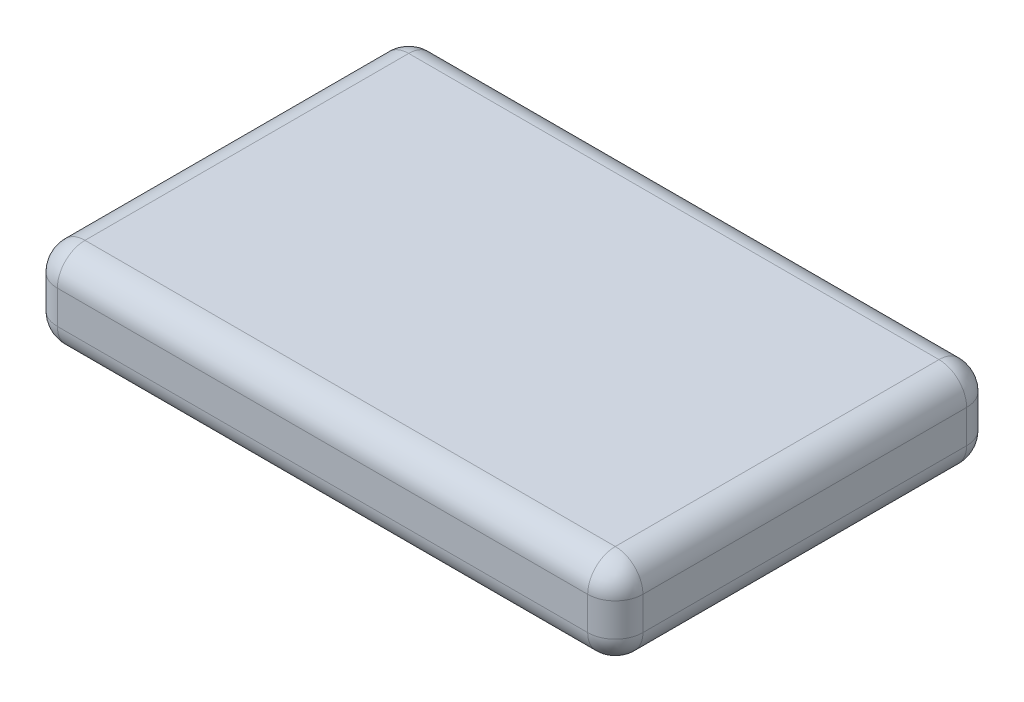
SolidWorks part; units mm, degrees
ref_plane "Front Plane" through (0, 0, 0) normal (0, 0, 1) x (1, 0, 0)
ref_plane "Top Plane" through (0, 0, 0) normal (0, 1, 0) x (1, 0, 0)
ref_plane "Right Plane" through (0, 0, 0) normal (1, 0, 0) x (0, 0, -1)
sketch "Sketch1" plane through (0, 0, 0) normal (0, 1, 0) x (1, 0, 0)
  line L1 (-53, -34.3) -> (53, -34.3)
  line L2 (-53, -34.3) -> (-53, 34.3)
  line L3 (-53, 34.3) -> (53, 34.3)
  line L4 (53, -34.3) -> (53, 34.3)
  line L5 (-53, -34.3) -> (53, 34.3) construction
  line L6 (-53, 34.3) -> (53, -34.3) construction
  point P0 (0, 0)
  dimension "D1" = 106
  dimension "D2" = 68.6
extrude "Boss-Extrude1" add sketch "Sketch1" along normal mid plane 16
fillet "Fillet1" radius 5 4 edges at (-53, 0, -34.3) (53, 0, -34.3) (53, 0, 34.3) (-53, 0, 34.3)
fillet "Fillet2" radius 5 16 edges at (51.5355, -8, -32.8355) (53, -8, 0) (51.5355, -8, 32.8355) (0, -8, 34.3) (-51.5355, -8, 32.8355) (-53, -8, 0) (-51.5355, -8, -32.8355) (51.5355, 8, -32.8355) (53, 8, 0) (51.5355, 8, 32.8355) (0, 8, 34.3) (-51.5355, 8, 32.8355) (-53, 8, 0) (-51.5355, 8, -32.8355) (0, 8, -34.3) (0, -8, -34.3)
